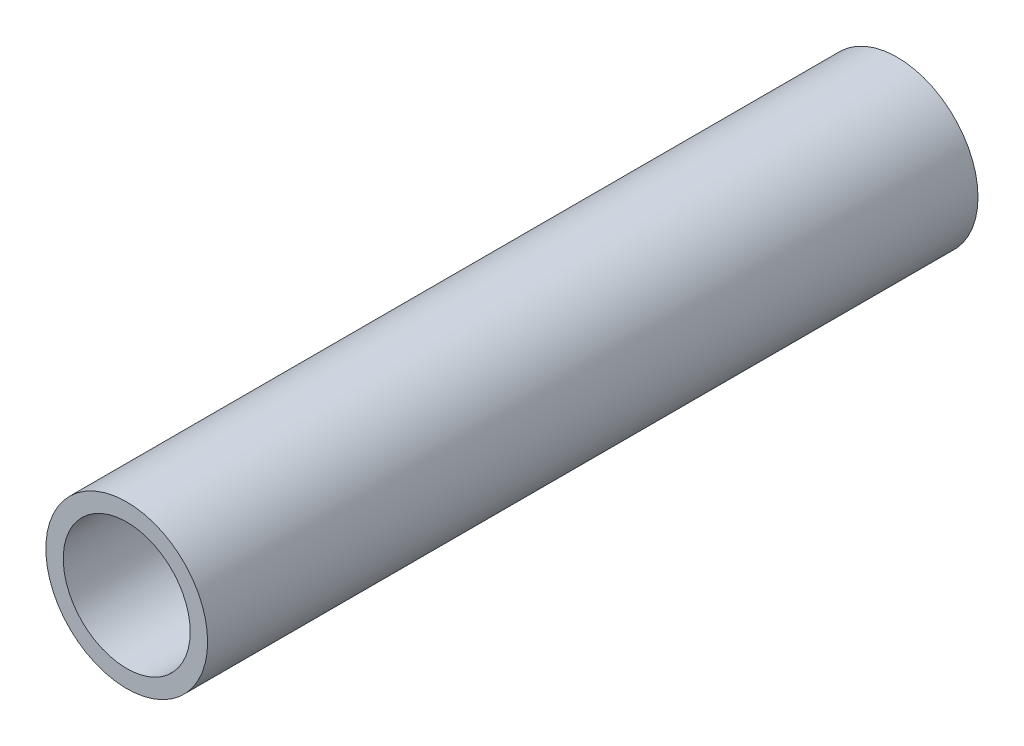
SolidWorks part; units mm, degrees
ref_plane "Front Plane" through (0, 0, 0) normal (0, 0, 1) x (1, 0, 0)
ref_plane "Top Plane" through (0, 0, 0) normal (0, 1, 0) x (1, 0, 0)
ref_plane "Right Plane" through (0, 0, 0) normal (1, 0, 0) x (0, 0, -1)
sketch "Sketch1" plane through (0, 0, 0) normal (0, 0, 1) x (1, 0, 0)
  circle A0 centre (0, 0) radius 10.4648
  circle A1 centre (0, 0) radius 13.335
  dimension "D1" = 2.8702
  dimension "D2" = 26.67
extrude "Boss-Extrude1" add sketch "Sketch1" along normal blind 127
